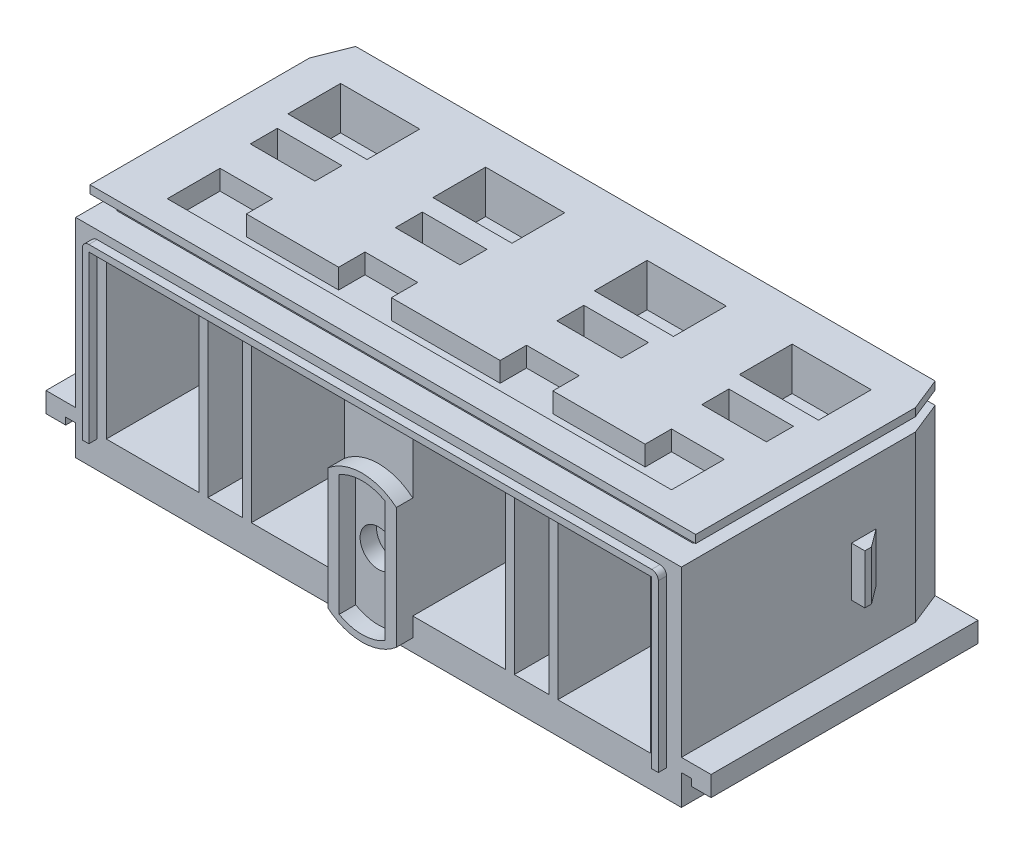
SolidWorks part; units mm, degrees
ref_plane "Alzado" through (0, 0, 0) normal (0, 0, 1) x (1, 0, 0)
ref_plane "Planta" through (0, 0, 0) normal (0, 1, 0) x (1, 0, 0)
ref_plane "Vista lateral" through (0, 0, 0) normal (1, 0, 0) x (0, 0, -1)
other "Centro de masa"
sketch "Croquis1" plane through (0, 0, 0) normal (0, 1, 0) x (1, 0, 0)
  line L0 (-45.95, -20.25) -> (-45.95, 15.25)
  line L5 (45.95, -20.25) -> (45.95, 15.25)
  line L6 (-45.95, -20.25) -> (45.95, -20.25)
  line L7 (-43.95, 20.25) -> (43.95, 20.25)
  line L8 (-45.95, 15.25) -> (-43.95, 20.25)
  line L9 (45.95, 15.25) -> (43.95, 20.25)
  line L10 (-45.95, -20.25) -> (45.95, 20.25) construction
  line L12 (45.95, -20.25) -> (-45.95, 20.25) construction
  point P5 (0, -20.25)
  point P7 (0, 20.25)
  point P9 (0, 0)
  dimension "D1" = 35.5
  dimension "D2" = 91.9
  dimension "D3" = 87.9
  dimension "D4" = 5
  dimension "D5" = 2
extrude "Cubo base" add sketch "Croquis1" along normal blind 31.59
ref_plane "Plano para extrucciones laterales" through (0, 0, 20.25) normal (0, 0, 1) x (1, 0, 0)
sketch "Croquis2" plane through (0, 0, 20.25) normal (0, 0, 1) x (1, 0, 0)
  line L0 (45.95, 31.59) -> (45.95, 0) construction
  line L1 (45.95, 6.59) -> (50.45, 6.59)
  line L3 (47.46, 3.54) -> (50.45, 3.54)
  line L4 (50.45, 6.59) -> (50.45, 3.54)
  line L5 (-45.95, 0) -> (45.95, 0) construction
  line L6 (0, 31.59) -> (0, 0) construction
  line L7 (-45.95, 31.59) -> (45.95, 31.59) construction
  line L8 (47.46, 4.59) -> (47.46, 3.54)
  line L9 (47.46, 4.59) -> (45.95, 4.59)
  line L10 (-50.45, 6.59) -> (-50.45, 3.54)
  line L11 (-47.46, 4.59) -> (-47.46, 3.54)
  line L12 (-47.46, 3.54) -> (-50.45, 3.54)
  line L14 (-47.46, 4.59) -> (-45.95, 4.59)
  line L15 (-45.95, 6.59) -> (-50.45, 6.59)
  line L16 (45.95, 6.59) -> (43.95, 6.59)
  line L17 (43.95, 6.59) -> (43.95, 4.59)
  line L18 (43.95, 4.59) -> (45.95, 4.59)
  line L19 (-45.95, 6.59) -> (-43.95, 6.59)
  line L20 (-43.95, 6.59) -> (-43.95, 4.59)
  line L21 (-43.95, 4.59) -> (-45.95, 4.59)
  dimension "D1" = 3.05
  dimension "D2" = 4.5
  dimension "D3" = 6.59
  dimension "D4" = 2.99
  dimension "D5" = 4.59
  dimension "D6" = 3.54
  dimension "D7" = 2
  dimension "D8" = 2
extrude "Guias laterales" add sketch "Croquis2" against normal blind 40.5
ref_plane "Trabas Laterales" through (0, 21.84, 0) normal (0, 1, 0) x (1, 0, 0)
sketch "Croquis3" plane through (0, 21.84, 0) normal (0, 1, 0) x (1, 0, 0)
  line L0 (-45.95, 9.2801) -> (-45.95, 5.55)
  line L1 (-45.95, 15.25) -> (-45.95, -20.25) construction
  line L2 (-45.95, 15.25) -> (-45.95, -20.25) construction
  line L3 (-45.95, 5.55) -> (-47.98, 5.55)
  line L4 (-47.98, 5.55) -> (-47.98, 6.55)
  line L5 (-47.98, 6.55) -> (-45.95, 9.2801)
  line L11 (-43.95, 20.25) -> (-50.45, 20.25) construction
  line L12 (0, 20.25) -> (0, -20.25) construction
  line L13 (43.95, 20.25) -> (-43.95, 20.25) construction
  line L14 (-45.95, -20.25) -> (45.95, -20.25) construction
  line L15 (45.95, 5.55) -> (47.98, 5.55)
  line L16 (47.98, 5.55) -> (47.98, 6.55)
  line L17 (47.98, 6.55) -> (45.95, 9.2801)
  line L18 (45.95, 9.2801) -> (45.95, 5.55)
  dimension "D1" = 1
  dimension "D2" = 14.7
  dimension "D3" = 2.7301
  dimension "D4" = 2.03
extrude "Trabas_Laterales" add sketch "Croquis3" against normal blind 7.5
sketch "Croquis4" plane through (0, 31.59, 0) normal (0, 1, 0) x (1, 0, 0)
  line L0 (43.95, 20.25) -> (-43.95, 20.25) construction
  line L1 (-43.7, 17.25) -> (43.7, 17.25)
  line L2 (-43.7, 17.25) -> (-43.7, -16.25)
  line L3 (-43.7, -16.25) -> (43.7, -16.25)
  line L4 (43.7, 17.25) -> (43.7, -16.25)
  line L5 (45.95, -20.25) -> (45.95, 15.25) construction
  line L6 (-45.95, 15.25) -> (-45.95, -20.25) construction
  line L7 (-45.95, -20.25) -> (45.95, -20.25) construction
  dimension "D1" = 3
  dimension "D2" = 87.4
  dimension "D3" = 2.25
  dimension "D4" = 2.25
  dimension "D5" = 4
extrude "Burlete" add sketch "Croquis4" along normal blind 2
sketch "Croquis5" plane through (0, 33.59, 0) normal (0, 1, 0) x (1, 0, 0)
  line L0 (-45.95, 15.25) -> (-43.95, 20.25)
  line L2 (-43.95, 20.25) -> (43.95, 20.25)
  line L3 (43.95, 20.25) -> (45.95, 15.25)
  line L4 (45.95, 15.25) -> (45.95, -18.08)
  line L5 (45.95, -20.25) -> (45.95, 15.25) construction
  line L6 (45.95, -18.08) -> (-45.95, -18.08)
  line L7 (-45.95, 15.25) -> (-45.95, -20.25) construction
  line L8 (-45.95, -18.08) -> (-45.95, 15.25)
  line L9 (-43.7, -16.25) -> (43.7, -16.25) construction
  dimension "D1" = 1.83
extrude "Tapa Superior" add sketch "Croquis5" along normal blind 1.2
sketch "Croquis6" plane through (0, 0, -20.25) normal (0, 0, -1) x (-1, 0, 0)
  line L0 (-43.95, 34.79) -> (43.95, 34.79) construction
  line L8 (-41.5, 29.17) -> (41.5, 29.17)
  line L9 (-41.5, 29.17) -> (-41.5, 3.17)
  line L10 (-41.5, 3.17) -> (41.5, 3.17)
  line L11 (41.5, 29.17) -> (41.5, 3.17)
  dimension "D1" = 83
  dimension "D2" = 26
  dimension "D3" = 5.62
extrude "Corte Trasero" [suppressed] cut sketch "Croquis6" against normal blind 1
sketch "Croquis7" plane through (0, 0, 0) normal (0, -1, 0) x (1, 0, 0)
  line L0 (-34.25, -8) -> (50.45, -8) construction
  line L1 (-43, 17.25) -> (43, 17.25)
  line L2 (-44, 16.25) -> (-44, -16.25)
  line L3 (-43, -17.25) -> (43, -17.25)
  line L4 (44, 16.25) -> (44, -16.25)
  line L5 (0, 20.25) -> (0, -20.25) construction
  line L6 (-45.95, 20.25) -> (45.95, 20.25) construction
  line L7 (43.95, -20.25) -> (-43.95, -20.25) construction
  line L12 (-40.5, -1) -> (-28, -1)
  line L13 (-41.5, -2) -> (-41.5, -14)
  line L14 (-40.5, -15) -> (-28, -15)
  line L15 (-27, -2) -> (-27, -14)
  line L16 (-41.5, -1) -> (-27, -15) construction
  line L17 (-41.5, -15) -> (-27, -1) construction
  line L19 (-38.1696, -3.25) -> (-30.3304, -3.25)
  line L20 (-39.1696, -4.25) -> (-39.1696, -11.75)
  line L21 (-38.1696, -12.75) -> (-30.3304, -12.75)
  line L22 (-29.3304, -4.25) -> (-29.3304, -11.75)
  line L23 (-39.1696, -3.25) -> (-29.3304, -12.75) construction
  line L24 (-39.1696, -12.75) -> (-29.3304, -3.25) construction
  line L25 (50.45, -20.25) -> (50.45, 20.25) construction
  line L26 (-23.25, -1) -> (-23.25, -15) construction
  line L29 (-17.1696, -4.25) -> (-17.1696, -11.75)
  line L30 (-8.3304, -3.25) -> (-16.1696, -3.25)
  line L31 (-7.3304, -4.25) -> (-7.3304, -11.75)
  line L33 (-8.3304, -12.75) -> (-16.1696, -12.75)
  line L34 (-6, -15) -> (-18.5, -15)
  line L35 (-19.5, -2) -> (-19.5, -14)
  line L36 (-6, -1) -> (-18.5, -1)
  line L37 (-5, -2) -> (-5, -14)
  line L43 (34.25, -8) -> (-50.45, -8) construction
  line L44 (5, -2) -> (5, -14)
  line L45 (6, -1) -> (18.5, -1)
  line L46 (19.5, -2) -> (19.5, -14)
  line L47 (6, -15) -> (18.5, -15)
  line L48 (8.3304, -12.75) -> (16.1696, -12.75)
  line L49 (7.3304, -4.25) -> (7.3304, -11.75)
  line L50 (8.3304, -3.25) -> (16.1696, -3.25)
  line L51 (17.1696, -4.25) -> (17.1696, -11.75)
  line L52 (29.3304, -4.25) -> (29.3304, -11.75)
  line L53 (38.1696, -12.75) -> (30.3304, -12.75)
  line L54 (39.1696, -4.25) -> (39.1696, -11.75)
  line L55 (38.1696, -3.25) -> (30.3304, -3.25)
  line L56 (27, -2) -> (27, -14)
  line L57 (40.5, -15) -> (28, -15)
  line L58 (41.5, -2) -> (41.5, -14)
  line L59 (40.5, -1) -> (28, -1)
  arc A0 (43, 17.25) -> (44, 16.25) centre (43, 16.25) cw
  arc A1 (43, -17.25) -> (44, -16.25) centre (43, -16.25) ccw
  arc A2 (-44, -16.25) -> (-43, -17.25) centre (-43, -16.25) ccw
  arc A3 (-43, 17.25) -> (-44, 16.25) centre (-43, 16.25) ccw
  arc A4 (-38.1696, -3.25) -> (-39.1696, -4.25) centre (-38.1696, -4.25) ccw
  arc A5 (-39.1696, -11.75) -> (-38.1696, -12.75) centre (-38.1696, -11.75) ccw
  arc A6 (-30.3304, -12.75) -> (-29.3304, -11.75) centre (-30.3304, -11.75) ccw
  arc A7 (-30.3304, -3.25) -> (-29.3304, -4.25) centre (-30.3304, -4.25) cw
  arc A8 (-28, -1) -> (-27, -2) centre (-28, -2) cw
  arc A9 (-28, -15) -> (-27, -14) centre (-28, -14) ccw
  arc A10 (-41.5, -14) -> (-40.5, -15) centre (-40.5, -14) ccw
  arc A11 (-40.5, -1) -> (-41.5, -2) centre (-40.5, -2) ccw
  arc A12 (-16.1696, -12.75) -> (-17.1696, -11.75) centre (-16.1696, -11.75) cw
  arc A13 (-16.1696, -3.25) -> (-17.1696, -4.25) centre (-16.1696, -4.25) ccw
  arc A14 (-8.3304, -3.25) -> (-7.3304, -4.25) centre (-8.3304, -4.25) cw
  arc A15 (-5, -14) -> (-6, -15) centre (-6, -14) cw
  arc A16 (-7.3304, -11.75) -> (-8.3304, -12.75) centre (-8.3304, -11.75) cw
  arc A17 (-18.5, -15) -> (-19.5, -14) centre (-18.5, -14) cw
  arc A18 (-18.5, -1) -> (-19.5, -2) centre (-18.5, -2) ccw
  arc A19 (-6, -1) -> (-5, -2) centre (-6, -2) cw
  arc A20 (6, -1) -> (5, -2) centre (6, -2) ccw
  arc A21 (18.5, -1) -> (19.5, -2) centre (18.5, -2) cw
  arc A22 (18.5, -15) -> (19.5, -14) centre (18.5, -14) ccw
  arc A23 (7.3304, -11.75) -> (8.3304, -12.75) centre (8.3304, -11.75) ccw
  arc A24 (5, -14) -> (6, -15) centre (6, -14) ccw
  arc A25 (8.3304, -3.25) -> (7.3304, -4.25) centre (8.3304, -4.25) ccw
  arc A26 (16.1696, -3.25) -> (17.1696, -4.25) centre (16.1696, -4.25) cw
  arc A27 (16.1696, -12.75) -> (17.1696, -11.75) centre (16.1696, -11.75) ccw
  arc A28 (40.5, -1) -> (41.5, -2) centre (40.5, -2) cw
  arc A29 (41.5, -14) -> (40.5, -15) centre (40.5, -14) cw
  arc A30 (28, -15) -> (27, -14) centre (28, -14) cw
  arc A31 (28, -1) -> (27, -2) centre (28, -2) ccw
  arc A32 (30.3304, -3.25) -> (29.3304, -4.25) centre (30.3304, -4.25) ccw
  arc A33 (30.3304, -12.75) -> (29.3304, -11.75) centre (30.3304, -11.75) cw
  arc A34 (39.1696, -11.75) -> (38.1696, -12.75) centre (38.1696, -11.75) cw
  arc A35 (38.1696, -3.25) -> (39.1696, -4.25) centre (38.1696, -4.25) cw
  point P20 (-41.5, -8)
  point P23 (-34.25, -8)
  point P24 (-34.25, -8)
  point P58 (-12.25, -8)
  point P59 (12.25, -8)
  point P60 (34.25, -8)
  dimension "D3" = 1
  dimension "D9" = 1
  dimension "D1" = 22
  dimension "D4" = 12.25
  dimension "D5" = 14
  dimension "D6" = 14.5
  dimension "D7" = 12.25
  dimension "D8" = 9.5
  dimension "D10" = 22
  dimension "D11" = 11
extrude "Borneras" cut sketch "Croquis7" against normal blind 1.44
sketch "Croquis8" plane through (0, 0, 20.25) normal (0, 0, 1) x (1, 0, 0)
  line L0 (-45.95, 0) -> (45.95, 0) construction
  line L1 (-42.7, 30.29) -> (42.7, 30.29)
  line L2 (-43.7, 29.29) -> (-43.7, 4.09)
  line L4 (43.7, 29.29) -> (43.7, 4.09)
  line L5 (-43.7, 4.09) -> (-42.7, 4.09)
  line L6 (43.7, 4.09) -> (42.7, 4.09)
  line L7 (-45.95, 31.59) -> (-45.95, 6.59) construction
  line L8 (0, 30.29) -> (0, 4.09) construction
  line L9 (-43.7, 16.69) -> (43.7, 16.69) construction
  line L11 (-42.7, 29.29) -> (42.7, 29.29)
  line L12 (-42.7, 29.29) -> (-42.7, 4.09)
  line L14 (42.7, 29.29) -> (42.7, 4.09)
  line L15 (-42.7, 29.29) -> (42.7, 4.09) construction
  line L16 (-42.7, 4.09) -> (42.7, 29.29) construction
  arc A0 (42.7, 30.29) -> (43.7, 29.29) centre (42.7, 29.29) cw
  arc A1 (-42.7, 30.29) -> (-43.7, 29.29) centre (-42.7, 29.29) ccw
  point P8 (43.7, 30.29)
  point P13 (-43.7, 30.29)
  point P18 (0, 16.69)
  dimension "D5" = 1
  dimension "D1" = 30.29
  dimension "D2" = 87.4
  dimension "D3" = 26.2
  dimension "D4" = 2.25
  dimension "D6" = 1
  dimension "D7" = 1
extrude "Saliente_Frontal" add sketch "Croquis8" along normal blind 1.25
sketch "Croquis9" plane through (0, 0, 20.25) normal (0, 0, 1) x (1, 0, 0)
  line L0 (27.2, 4.79) -> (27.2, 29.29)
  line L3 (41.3, 4.79) -> (27.2, 4.79)
  line L9 (-42.7, 29.29) -> (42.7, 29.29) construction
  line L14 (0, 29.29) -> (0, 0) construction
  line L15 (-45.95, 0) -> (45.95, 0) construction
  line L39 (40.5, 1.44) -> (28, 1.44) construction
  line L40 (40.5, 1.44) -> (28, 1.44) construction
  line L41 (6, 1.44) -> (18.5, 1.44) construction
  line L42 (6, 1.44) -> (18.5, 1.44) construction
  line L43 (-6, 1.44) -> (-18.5, 1.44) construction
  line L44 (-6, 1.44) -> (-18.5, 1.44) construction
  line L45 (-40.5, 1.44) -> (-28, 1.44) construction
  line L46 (-40.5, 1.44) -> (-28, 1.44) construction
  line L47 (27.2, 29.29) -> (41.3, 29.29)
  line L48 (41.3, 29.29) -> (41.3, 4.79)
  line L49 (23.25, 1.44) -> (23.25, 22.842) construction
  line L50 (5.2, 4.79) -> (19.3, 4.79)
  line L51 (5.2, 29.29) -> (5.2, 4.79)
  line L52 (19.3, 29.29) -> (5.2, 29.29)
  line L53 (19.3, 4.79) -> (19.3, 29.29)
  line L54 (-41.3, 4.79) -> (-27.2, 4.79)
  line L55 (-41.3, 29.29) -> (-41.3, 4.79)
  line L56 (-27.2, 4.79) -> (-27.2, 29.29)
  line L57 (-27.2, 29.29) -> (-41.3, 29.29)
  line L58 (-19.3, 29.29) -> (-5.2, 29.29)
  line L59 (-19.3, 4.79) -> (-19.3, 29.29)
  line L60 (-5.2, 4.79) -> (-19.3, 4.79)
  line L61 (-5.2, 29.29) -> (-5.2, 4.79)
  line L62 (-25.9, 29.29) -> (-25.9, 4.79) construction
  line L63 (-20.6, 29.29) -> (-20.6, 4.79) construction
  line L64 (-25.9, 29.29) -> (-20.6, 29.29)
  line L65 (-20.6, 29.29) -> (-20.6, 4.79)
  line L66 (-20.6, 4.79) -> (-25.9, 4.79)
  line L67 (-25.9, 4.79) -> (-25.9, 29.29)
  line L68 (20.6, 29.29) -> (20.6, 4.79)
  line L69 (25.9, 29.29) -> (25.9, 4.79)
  line L70 (-42.7, 29.29) -> (42.7, 29.29) construction
  line L71 (25.9, 29.29) -> (20.6, 29.29)
  line L72 (20.6, 4.79) -> (25.9, 4.79)
  point P9 (34.25, 4.79)
  point P26 (34.25, 1.44)
  line M36 (42.7, 29.29) -> (-42.7, 29.29)
  dimension "D1" = 14.1
  dimension "D2" = 11
  dimension "D3" = 1.3
  dimension "D4" = 1.3
  dimension "D5" = 1.3
  dimension "D6" = 1.3
extrude "Corte en profundidad frontal" cut sketch "Croquis9" against normal blind 37.3 contours L54 L56 L55 M36 | L61 L59 L60 M36 | L50 L53 L51 M36 | L48 L0 L3 M36 | L67 L66 L65 M36 | L68 L72 L69 M36
sketch "Croquis13" plane through (0, 1.44, 0) normal (0, -1, 0) x (1, 0, 0)
  line L4 (-30.3304, -3.25) -> (-38.1696, -3.25)
  line L5 (-39.1696, -4.25) -> (-39.1696, -11.75)
  line L6 (-38.1696, -12.75) -> (-30.3304, -12.75)
  line L7 (-29.3304, -11.75) -> (-29.3304, -4.25)
  line L8 (-30.3304, -3.25) -> (-38.1696, -3.25)
  line L9 (-39.1696, -4.25) -> (-39.1696, -11.75)
  line L10 (-38.1696, -12.75) -> (-30.3304, -12.75)
  line L11 (-29.3304, -11.75) -> (-29.3304, -4.25)
  line L12 (-7.3304, -11.75) -> (-7.3304, -4.25)
  line L13 (-8.3304, -3.25) -> (-16.1696, -3.25)
  line L14 (-17.1696, -4.25) -> (-17.1696, -11.75)
  line L15 (-16.1696, -12.75) -> (-8.3304, -12.75)
  line L16 (-7.3304, -11.75) -> (-7.3304, -4.25)
  line L17 (-8.3304, -3.25) -> (-16.1696, -3.25)
  line L18 (-17.1696, -4.25) -> (-17.1696, -11.75)
  line L19 (-16.1696, -12.75) -> (-8.3304, -12.75)
  line L20 (8.3304, -12.75) -> (16.1696, -12.75)
  line L21 (17.1696, -11.75) -> (17.1696, -4.25)
  line L22 (16.1696, -3.25) -> (8.3304, -3.25)
  line L23 (7.3304, -4.25) -> (7.3304, -11.75)
  line L24 (8.3304, -12.75) -> (16.1696, -12.75)
  line L25 (17.1696, -11.75) -> (17.1696, -4.25)
  line L26 (16.1696, -3.25) -> (8.3304, -3.25)
  line L27 (7.3304, -4.25) -> (7.3304, -11.75)
  line L28 (38.1696, -3.25) -> (30.3304, -3.25)
  line L29 (29.3304, -4.25) -> (29.3304, -11.75)
  line L30 (30.3304, -12.75) -> (38.1696, -12.75)
  line L31 (39.1696, -11.75) -> (39.1696, -4.25)
  line L32 (38.1696, -3.25) -> (30.3304, -3.25)
  line L33 (29.3304, -4.25) -> (29.3304, -11.75)
  line L34 (30.3304, -12.75) -> (38.1696, -12.75)
  line L35 (39.1696, -11.75) -> (39.1696, -4.25)
  arc A4 (-29.3304, -4.25) -> (-30.3304, -3.25) centre (-30.3304, -4.25) ccw
  arc A5 (-38.1696, -3.25) -> (-39.1696, -4.25) centre (-38.1696, -4.25) ccw
  arc A6 (-39.1696, -11.75) -> (-38.1696, -12.75) centre (-38.1696, -11.75) ccw
  arc A7 (-30.3304, -12.75) -> (-29.3304, -11.75) centre (-30.3304, -11.75) ccw
  arc A8 (-29.3304, -4.25) -> (-30.3304, -3.25) centre (-30.3304, -4.25) ccw
  arc A9 (-38.1696, -3.25) -> (-39.1696, -4.25) centre (-38.1696, -4.25) ccw
  arc A10 (-39.1696, -11.75) -> (-38.1696, -12.75) centre (-38.1696, -11.75) ccw
  arc A11 (-30.3304, -12.75) -> (-29.3304, -11.75) centre (-30.3304, -11.75) ccw
  arc A12 (-8.3304, -12.75) -> (-7.3304, -11.75) centre (-8.3304, -11.75) ccw
  arc A13 (-7.3304, -4.25) -> (-8.3304, -3.25) centre (-8.3304, -4.25) ccw
  arc A14 (-16.1696, -3.25) -> (-17.1696, -4.25) centre (-16.1696, -4.25) ccw
  arc A15 (-17.1696, -11.75) -> (-16.1696, -12.75) centre (-16.1696, -11.75) ccw
  arc A16 (-8.3304, -12.75) -> (-7.3304, -11.75) centre (-8.3304, -11.75) ccw
  arc A17 (-7.3304, -4.25) -> (-8.3304, -3.25) centre (-8.3304, -4.25) ccw
  arc A18 (-16.1696, -3.25) -> (-17.1696, -4.25) centre (-16.1696, -4.25) ccw
  arc A19 (-17.1696, -11.75) -> (-16.1696, -12.75) centre (-16.1696, -11.75) ccw
  arc A20 (16.1696, -12.75) -> (17.1696, -11.75) centre (16.1696, -11.75) ccw
  arc A21 (17.1696, -4.25) -> (16.1696, -3.25) centre (16.1696, -4.25) ccw
  arc A22 (8.3304, -3.25) -> (7.3304, -4.25) centre (8.3304, -4.25) ccw
  arc A23 (7.3304, -11.75) -> (8.3304, -12.75) centre (8.3304, -11.75) ccw
  arc A24 (16.1696, -12.75) -> (17.1696, -11.75) centre (16.1696, -11.75) ccw
  arc A25 (17.1696, -4.25) -> (16.1696, -3.25) centre (16.1696, -4.25) ccw
  arc A26 (8.3304, -3.25) -> (7.3304, -4.25) centre (8.3304, -4.25) ccw
  arc A27 (7.3304, -11.75) -> (8.3304, -12.75) centre (8.3304, -11.75) ccw
  arc A28 (39.1696, -4.25) -> (38.1696, -3.25) centre (38.1696, -4.25) ccw
  arc A29 (30.3304, -3.25) -> (29.3304, -4.25) centre (30.3304, -4.25) ccw
  arc A30 (29.3304, -11.75) -> (30.3304, -12.75) centre (30.3304, -11.75) ccw
  arc A31 (38.1696, -12.75) -> (39.1696, -11.75) centre (38.1696, -11.75) ccw
  arc A32 (39.1696, -4.25) -> (38.1696, -3.25) centre (38.1696, -4.25) ccw
  arc A33 (30.3304, -3.25) -> (29.3304, -4.25) centre (30.3304, -4.25) ccw
  arc A34 (29.3304, -11.75) -> (30.3304, -12.75) centre (30.3304, -11.75) ccw
  arc A35 (38.1696, -12.75) -> (39.1696, -11.75) centre (38.1696, -11.75) ccw
  dimension "D1" = 0
  dimension "D2" = 0
  dimension "D3" = 0
  dimension "D4" = 0
extrude "Corte en profundidad inferior" cut sketch "Croquis13" against normal blind 5
sketch "Croquis14" plane through (0, 0, 20.25) normal (0, 0, 1) x (1, 0, 0)
  line L0 (-3.4699, 20.29) -> (-3.4699, 1.9205)
  line L1 (-5.2, 29.29) -> (-5.2, 4.79) construction
  line L2 (5.2, 29.29) -> (5.2, 4.79) construction
  line L3 (-45.95, 0) -> (45.95, 0) construction
  line L6 (-5.2, 20.29) -> (-5.2, 1.9205)
  line L8 (5.2, 20.29) -> (5.2, 1.9205)
  line L9 (-5.2, 20.29) -> (5.2, 20.29) construction
  line L14 (-5.2, 20.29) -> (-5.2, 1.9205) construction
  line L15 (-5.2, 1.9205) -> (5.2, 1.9205) construction
  line L16 (5.2, 20.29) -> (5.2, 1.9205) construction
  line L17 (3.4699, 20.29) -> (3.4699, 1.9205)
  arc A0 (-5.2, 20.29) -> (5.2, 20.29) centre (0, 14.2105) cw
  arc A1 (-5.2, 1.9205) -> (5.2, 1.9205) centre (0, 8) ccw
  arc A2 (-3.4699, 20.29) -> (3.4699, 20.29) centre (0, 14.2105) cw
  arc A3 (3.4699, 1.9205) -> (-3.4699, 1.9205) centre (0, 8) cw
  dimension "D2" = 8
  dimension "D1" = 7
  dimension "D3" = 7
extrude "Tornillo" add sketch "Croquis14" along normal blind 2.5
sketch "Croquis15" plane through (0, 0, 20.25) normal (0, 0, 1) x (1, 0, 0)
  line L0 (0, 21.2105) -> (0, 1) construction
  arc A0 (3.4699, 20.29) -> (-3.4699, 20.29) centre (0, 14.2105) ccw construction
  arc A1 (-3.4699, 1.9205) -> (3.4699, 1.9205) centre (0, 8) ccw construction
  circle A2 centre (0, 11.1053) radius 2.8
  dimension "D1" = 5.6
extrude "Tornillo2" cut sketch "Croquis15" against normal blind 2.5
sketch "Croquis16" plane through (-41.3, 0, 0) normal (1, 0, 0) x (0, 0, -1)
  line L0 (-10.66, 29.29) -> (-5.95, 26.47)
  line L2 (17.05, 29.29) -> (-20.25, 29.29) construction
  line L3 (-5.95, 26.47) -> (17.05, 26.47)
  line L4 (17.05, 29.29) -> (17.05, 4.79) construction
  line L5 (17.05, 26.47) -> (17.05, 29.29)
  line L6 (17.05, 29.29) -> (-10.66, 29.29)
  dimension "D1" = 4.71
  dimension "D2" = 2.82
  dimension "D3" = 23
extrude "InteriorBorne" add sketch "Croquis16" along normal up to surface (82.6 mm away) up to face at (41.3, 17.04, 1.6)
sketch "Croquis17" plane through (0, 34.79, 0) normal (0, 1, 0) x (1, 0, 0)
  line L0 (-41.3, -20.25) -> (-27.2, -20.25) construction
  line L1 (-41.3, -20.25) -> (-27.2, -20.25) construction
  line L2 (-5.2, -20.25) -> (-19.3, -20.25) construction
  line L3 (-5.2, -20.25) -> (-19.3, -20.25) construction
  line L4 (5.2, -20.25) -> (19.3, -20.25) construction
  line L5 (5.2, -20.25) -> (19.3, -20.25) construction
  line L6 (41.3, -20.25) -> (27.2, -20.25) construction
  line L7 (41.3, -20.25) -> (27.2, -20.25) construction
  line L8 (43.95, 20.25) -> (-43.95, 20.25) construction
  line L9 (-39.15, 3.55) -> (-29.35, 3.55)
  line L10 (-39.15, 3.55) -> (-39.15, -0.55)
  line L11 (-39.15, -0.55) -> (-29.35, -0.55)
  line L12 (-29.35, 3.55) -> (-29.35, -0.55)
  line L13 (-23.25, 3.55) -> (-23.25, -0.55) construction
  line L14 (0, 0) -> (0, 3.55) construction
  line L15 (-17.15, 3.55) -> (-17.15, -0.55)
  line L16 (-7.35, -0.55) -> (-17.15, -0.55)
  line L17 (-7.35, 3.55) -> (-17.15, 3.55)
  line L18 (-7.35, 3.55) -> (-7.35, -0.55)
  line L19 (7.35, 3.55) -> (7.35, -0.55)
  line L20 (7.35, -0.55) -> (17.15, -0.55)
  line L21 (7.35, 3.55) -> (17.15, 3.55)
  line L22 (17.15, 3.55) -> (17.15, -0.55)
  line L23 (39.15, -0.55) -> (29.35, -0.55)
  line L24 (29.35, 3.55) -> (29.35, -0.55)
  line L25 (39.15, 3.55) -> (29.35, 3.55)
  line L26 (39.15, 3.55) -> (39.15, -0.55)
  point P14 (-34.25, -0.55)
  point P15 (-34.25, -20.25)
  point P16 (-12.25, -20.25)
  point P17 (12.25, -20.25)
  dimension "D1" = 4.1
  dimension "D2" = 9.8
  dimension "D3" = 16.7
  dimension "D4" = 22
  dimension "D5" = 24.5
  dimension "D6" = 11
extrude "BorneSuperior" cut sketch "Croquis17" against normal blind 10
sketch "Croquis18" plane through (0, 34.79, 0) normal (0, 1, 0) x (1, 0, 0)
  line L0 (-29.35, 3.55) -> (-39.15, 3.55) construction
  line L1 (-40.25, 14.25) -> (-28.25, 14.25)
  line L2 (-40.25, 14.25) -> (-40.25, 6.25)
  line L3 (-40.25, 6.25) -> (-28.25, 6.25)
  line L4 (-28.25, 14.25) -> (-28.25, 6.25)
  line L5 (43.95, 20.25) -> (-43.95, 20.25) construction
  line L6 (-23.25, 6.25) -> (-23.25, 14.25) construction
  line L7 (0, 7.9696) -> (0, 16.0829) construction
  line L8 (-6.25, 6.25) -> (-18.25, 6.25)
  line L9 (-18.25, 14.25) -> (-18.25, 6.25)
  line L10 (-6.25, 14.25) -> (-18.25, 14.25)
  line L11 (-6.25, 14.25) -> (-6.25, 6.25)
  line L12 (40.25, 6.25) -> (28.25, 6.25)
  line L13 (40.25, 14.25) -> (40.25, 6.25)
  line L14 (40.25, 14.25) -> (28.25, 14.25)
  line L15 (28.25, 14.25) -> (28.25, 6.25)
  line L16 (18.25, 14.25) -> (18.25, 6.25)
  line L17 (6.25, 6.25) -> (18.25, 6.25)
  line L18 (6.25, 14.25) -> (18.25, 14.25)
  line L19 (6.25, 14.25) -> (6.25, 6.25)
  point P6 (-34.25, 3.55)
  point P7 (-34.25, 6.25)
  point P19 (-12.25, 6.25)
  dimension "D1" = 8
  dimension "D2" = 12
  dimension "D3" = 6
  dimension "D4" = 11
  dimension "D5" = 12.25
extrude "Cortar-Extruir8" cut sketch "Croquis18" against normal blind 6.5
sketch "Croquis19" plane through (0, 34.79, 0) normal (0, 1, 0) x (1, 0, 0)
  line L0 (-8.25, -14.05) -> (8.25, -14.05)
  line L1 (-38.25, -6.05) -> (-30.25, -6.05)
  line L2 (-38.25, -6.05) -> (-38.25, -14.05)
  line L3 (-38.25, -14.05) -> (-23.25, -14.05)
  line L4 (-30.25, -6.05) -> (-30.25, -10.05)
  line L5 (29.35, -0.55) -> (39.15, -0.55) construction
  line L6 (7.35, -0.55) -> (17.15, -0.55) construction
  line L7 (-17.15, -0.55) -> (-7.35, -0.55) construction
  line L8 (-39.15, -0.55) -> (-29.35, -0.55) construction
  line L9 (29.35, -0.55) -> (39.15, -0.55) construction
  line L10 (7.35, -0.55) -> (17.15, -0.55) construction
  line L11 (-17.15, -0.55) -> (-7.35, -0.55) construction
  line L12 (-39.15, -0.55) -> (-29.35, -0.55) construction
  line L13 (0, -5.0671) -> (0, -14.05) construction
  line L14 (-23.25, -6.05) -> (-23.25, -14.05) construction
  line L15 (-8.25, -14.05) -> (-23.25, -14.05)
  line L16 (-16.25, -6.05) -> (-16.25, -10.05)
  line L17 (-8.25, -6.05) -> (-8.25, -10.05)
  line L18 (-8.25, -6.05) -> (-16.25, -6.05)
  line L19 (8.25, -14.05) -> (23.25, -14.05)
  line L20 (8.25, -6.05) -> (8.25, -10.05)
  line L21 (16.25, -6.05) -> (16.25, -10.05)
  line L22 (8.25, -6.05) -> (16.25, -6.05)
  line L23 (30.25, -6.05) -> (30.25, -10.05)
  line L24 (38.25, -14.05) -> (23.25, -14.05)
  line L25 (38.25, -6.05) -> (30.25, -6.05)
  line L26 (38.25, -6.05) -> (38.25, -14.05)
  line L27 (-30.25, -10.05) -> (-16.25, -10.05)
  line L28 (-8.25, -10.05) -> (8.25, -10.05)
  line L29 (16.25, -10.05) -> (30.25, -10.05)
  point P5 (-34.25, -0.55)
  point P6 (-34.25, -6.05)
  dimension "D1" = 8
  dimension "D2" = 8
  dimension "D3" = 5.5
  dimension "D4" = 11
extrude "Cortar-Extruir9" cut sketch "Croquis19" against normal blind 3
